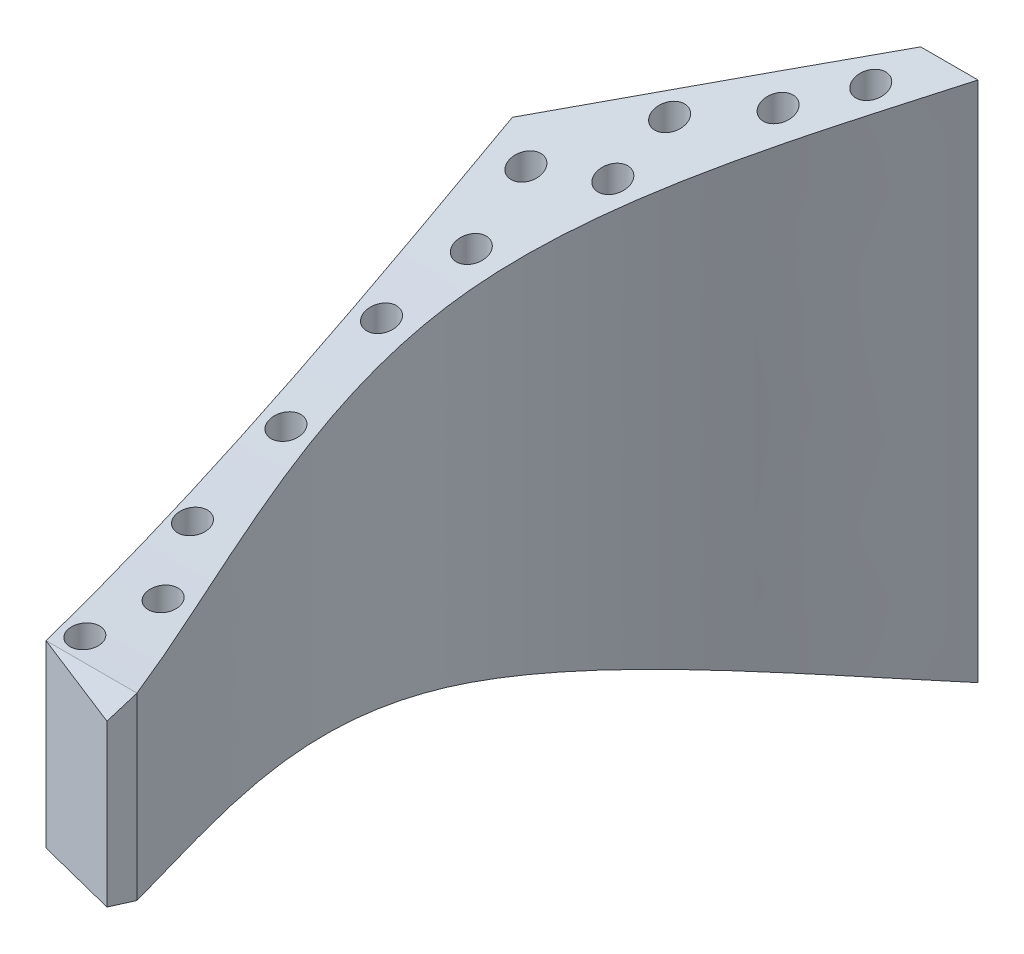
SolidWorks part; units mm, degrees
ref_plane "前视基准面" through (0, 0, 0) normal (0, 0, 1) x (1, 0, 0)
ref_plane "上视基准面" through (0, 0, 0) normal (0, 1, 0) x (1, 0, 0)
ref_plane "右视基准面" through (0, 0, 0) normal (1, 0, 0) x (0, 0, -1)
other "Configuration Table"
sketch "草图1" plane through (0, 0, 0) normal (0, 1, 0) x (1, 0, 0)
  line L4 (-11.381, 63.0174) -> (-31.4592, 41.8787)
  line L5 (-31.4592, 41.8787) -> (-20.9066, -15.7492)
  line L6 (-11.381, 63.0174) -> (-5.5987, 63.0174)
  line L7 (-20.9066, -15.7492) -> (-11.7237, -15.7492)
  spline S0 degree 3 poles (-11.7237, -15.7492) (-16.2692, -2.4836) (-30.4491, 26.4249) (-12.1596, 52.2488) (-5.5987, 63.0174) knots 0 0 0 0 0.528076 1 1 1 1
  point P4 (-17.4927, 0)
extrude "凸台-拉伸1" add sketch "草图1" along normal blind 52.687
ref_plane "基准面1" through (-31.4592, 0, 0) normal (1, 0, 0) x (0, 0, -1)
sketch "草图3" plane through (-31.4592, 0, 0) normal (1, 0, 0) x (0, 0, -1)
  line L0 (-15.7492, 26.3435) -> (63.0174, 26.3435)
  line L1 (63.0174, 52.687) -> (63.0174, 0) construction
  line L2 (-15.7492, 52.687) -> (-15.7492, 35.407)
  line L3 (-15.7492, 52.687) -> (-15.7492, 0) construction
  line L4 (63.0174, 0) -> (-15.7492, 0)
  line L6 (-15.7492, 0) -> (-15.7492, 17.28)
  line L7 (63.0174, 52.687) -> (-15.7492, 52.687)
  spline S0 degree 3 poles (-15.7492, 35.407) (11.139, 37.8811) (37.0201, 45.9711) (63.0174, 52.687) knots 0 0 0 0 1 1 1 1
  spline S1 degree 3 poles (-15.7492, 17.28) (11.139, 14.8059) (37.0201, 6.7159) (63.0174, 0) knots 0 0 0 0 1 1 1 1
extrude "切除-拉伸1" cut sketch "草图3" along normal blind 139.687 contours L2 S0 L7 | S1 L6 L4
ref_plane "基准面2" through (0, 35.407, 0) normal (0, 1, 0) x (-1, 0, 0)
sketch "草图7" plane through (0, 35.407, 0) normal (0, 1, 0) x (-1, 0, 0)
  line L3 (11.7237, 15.7492) -> (11.7237, 18.779)
  line L4 (11.7237, 18.779) -> (20.9066, 15.7492)
  line L5 (11.7237, 15.7492) -> (20.9066, 15.7492)
extrude "凸台-拉伸3" add sketch "草图7" against normal up to vertex (18.127 mm away)
ref_plane "基准面3" through (-20.9066, 0, 0) normal (1, 0, 0) x (0, 0, -1)
sketch "草图9" plane through (-20.9066, 0, 0) normal (1, 0, 0) x (0, 0, -1)
  line L0 (-31.6037, 40.8415) -> (-36.2432, 25.8071)
  line L2 (-36.2432, 25.8071) -> (-31.6037, 25.8071)
  line L3 (-31.6037, 40.8415) -> (-31.6037, 25.8071)
sketch "草图12" plane through (-20.9066, 0, 0) normal (1, 0, 0) x (0, 0, -1)
  line L0 (-15.7492, 35.407) -> (-30.7792, 35.407)
  line L1 (-30.7792, 35.407) -> (-30.7792, 30.767)
  line L2 (-30.7792, 30.767) -> (-15.7492, 35.407)
  line L3 (-15.7492, 26.3435) -> (-33.7655, 26.3435)
  line L4 (-15.7492, 35.407) -> (-15.7492, 17.28) construction
  line L5 (-30.7792, 17.28) -> (-30.7792, 21.92)
  line L6 (-15.7492, 17.28) -> (-30.7792, 17.28)
  line L7 (-30.7792, 21.92) -> (-15.7492, 17.28)
extrude "切除-拉伸2" cut sketch "草图12" along normal blind 23.687 contours L1 L2 L0 | L7 L5 L6
sketch "草图15" plane through (0, 0, 0) normal (0, 1, 0) x (1, 0, 0)
  point P0 (-11.7889, 58.3824)
  point P2 (-15.8497, 53.0889)
  point P4 (-21.8684, 48.1579)
  point P6 (-21.0708, 41.6316)
  point P8 (-27.2345, 39.021)
  point P10 (-24.8415, 31.1169)
  point P12 (-25.4216, 22.6327)
  point P14 (-23.3912, 10.9579)
  point P16 (-21.8684, 0)
  point P18 (-17.6626, -7.1708)
  point P20 (-19.1129, -13.6246)
hole_wizard "Ø1.0mm 暗销孔1" positions "草图15" profile "草图14" hole size "Ø1.0" standard "ANSI Metric" end condition through all
sketch "草图14" plane through (-11.7889, 0, -58.3824) normal (1, 0, 0) x (0, 0, -1)
  line L0 (0, 0) -> (0, 63.5777)
  line L1 (0, 63.5777) -> (1.5, 63.5777)
  line L2 (1.5, 63.5777) -> (1.5, 0)
  line L5 (1.5, 0) -> (0, 0)
  line L11 (0, -6.35) -> (0, 107.95) construction
  dimension "通孔孔直径" = 3
  dimension "通孔孔深度" = 63.5777
